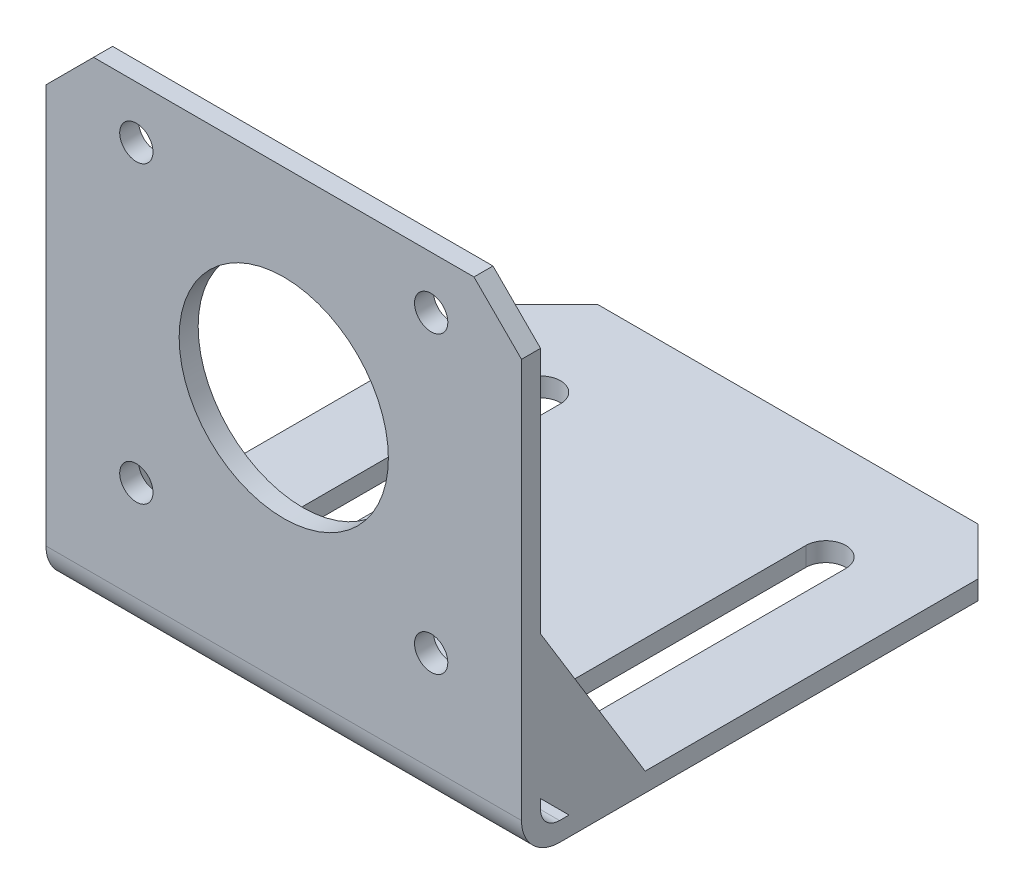
SolidWorks part; units mm, degrees
ref_plane "Front Plane" through (0, 0, 0) normal (0, 0, 1) x (1, 0, 0)
ref_plane "Top Plane" through (0, 0, 0) normal (0, 1, 0) x (1, 0, 0)
ref_plane "Right Plane" through (0, 0, 0) normal (1, 0, 0) x (0, 0, -1)
sketch "Sketch1" plane through (0, 0, 0) normal (1, 0, 0) x (0, 0, -1)
  line L0 (0, 51) -> (0, 4)
  line L1 (4, 0) -> (53, 0)
  line L2 (2, 51) -> (2, 4)
  line L3 (4, 2) -> (53, 2)
  line L4 (0, 51) -> (2, 51)
  line L5 (53, 0) -> (53, 2)
  arc A0 (4, 0) -> (0, 4) centre (4, 4) cw
  arc A1 (4, 2) -> (2, 4) centre (4, 4) cw
  point P6 (0, 0)
  dimension "D3" = 4
  dimension "D1" = 51
  dimension "D2" = 53
  dimension "D4" = 2
extrude "Boss-Extrude1" add sketch "Sketch1" against normal blind 50
sketch "Sketch2" plane through (0, 0, 0) normal (1, 0, 0) x (0, 0, -1)
  line L0 (2, 20) -> (13, 2)
  line L1 (2, 4) -> (2, 51) construction
  line L2 (53, 2) -> (4, 2) construction
  line L3 (13, 2) -> (5, 2)
  line L4 (5, 2) -> (2, 5)
  line L5 (2, 5) -> (2, 20)
  line L6 (4, 0) -> (53, 0) construction
  line L7 (0, 51) -> (0, 4) construction
  dimension "D1" = 20
  dimension "D2" = 13
  dimension "D3" = 15
  dimension "D4" = 8
extrude "Boss-Extrude2" add sketch "Sketch2" against normal blind 2
sketch "Sketch3" plane through (-50, 0, 0) normal (-1, 0, 0) x (0, 0, 1)
  line L0 (-2, 20) -> (-13, 2)
  line L1 (-13, 2) -> (-5, 2)
  line L2 (-5, 2) -> (-2, 5)
  line L3 (-2, 5) -> (-2, 20)
extrude "Boss-Extrude3" add sketch "Sketch3" against normal blind 2
sketch "Sketch4" plane through (0, 0, 0) normal (0, 0, 1) x (1, 0, 0)
  line L0 (-50, 51) -> (0, 51) construction
  line L1 (-50, 51) -> (-50, 4) construction
  line L2 (-25, 30) -> (-25, 45.5) construction
  line L3 (-25, 45.5) -> (-9.5, 45.5) construction
  circle A0 centre (-25, 30) radius 11
  circle A1 centre (-9.5, 45.5) radius 1.75
  circle A2 centre (-40.5, 45.5) radius 1.75
  circle A3 centre (-40.5, 14.5) radius 1.75
  circle A4 centre (-9.5, 14.5) radius 1.75
  dimension "D1" = 21
  dimension "D2" = 25
  dimension "D3" = 22
  dimension "D6" = 3.5
  dimension "D9" = 31
  dimension "D10" = 31
  dimension "D11" = 15.5
  dimension "D4" = 15.5
  dimension "D5" = 15.5
  dimension "D7" = 2
  dimension "D8" = 2
extrude "Cut-Extrude1" cut sketch "Sketch4" against normal blind 5
sketch "Sketch5" plane through (0, 0, 0) normal (0, -1, 0) x (1, 0, 0)
  line L0 (0, -4) -> (0, -53) construction
  line L1 (-50, -53) -> (0, -53) construction
  line L2 (-10, -42) -> (-10, -12) construction
  line L3 (-7.9, -42) -> (-7.9, -12)
  line L4 (-12.1, -12) -> (-12.1, -42)
  line L5 (-37.9, -42) -> (-37.9, -12)
  line L6 (-42.1, -12) -> (-42.1, -42)
  arc A0 (-12.1, -42) -> (-7.9, -42) centre (-10, -42) ccw
  arc A1 (-7.9, -12) -> (-12.1, -12) centre (-10, -12) ccw
  arc A2 (-37.9, -12) -> (-42.1, -12) centre (-40, -12) ccw
  arc A3 (-42.1, -42) -> (-37.9, -42) centre (-40, -42) ccw
  dimension "D1" = 10
  dimension "D2" = 11
  dimension "D3" = 4.2
  dimension "D5" = 4.2
  dimension "D9" = 30
  dimension "D4" = 30
  dimension "D6" = 30
  dimension "D7" = 30
  dimension "D8" = 2
extrude "Cut-Extrude2" cut sketch "Sketch5" against normal blind 5
chamfer "Chamfer1" distance 5 angle 45 4 edges at (0, 51, -1) (-50, 51, -1) (0, 1, -53) (-50, 1, -53)
